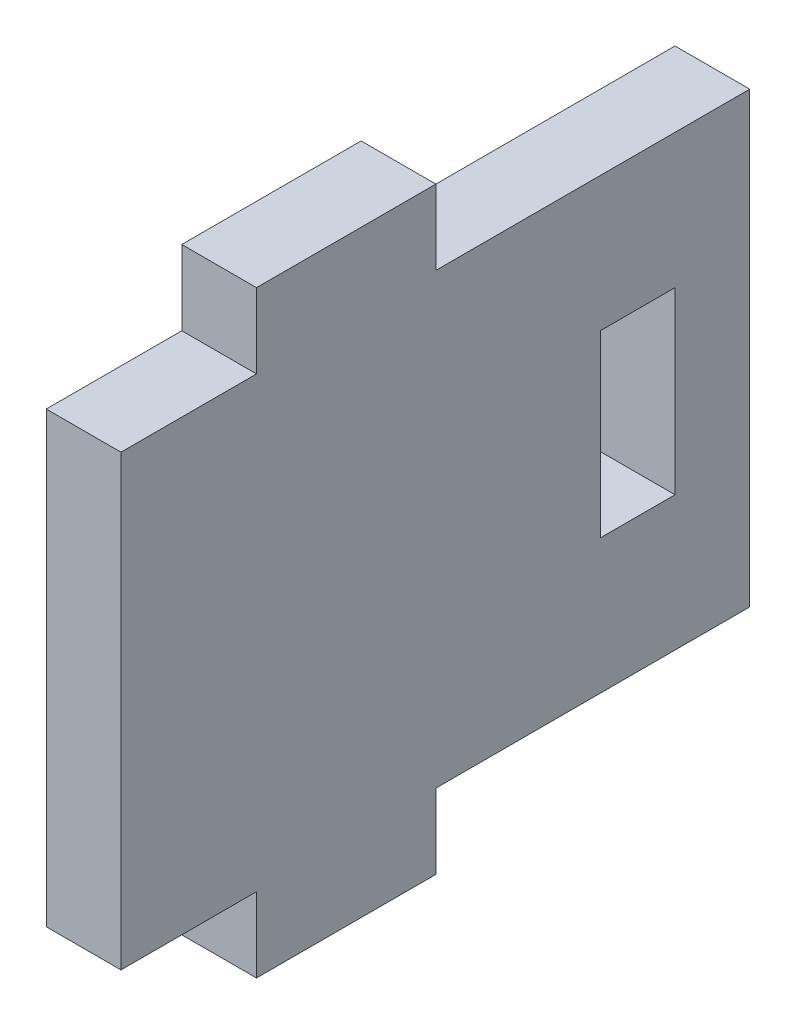
SolidWorks part; units mm, degrees
ref_plane "Front Plane" through (0, 0, 0) normal (0, 0, 1) x (1, 0, 0)
ref_plane "Top Plane" through (0, 0, 0) normal (0, 1, 0) x (1, 0, 0)
ref_plane "Right Plane" through (0, 0, 0) normal (1, 0, 0) x (0, 0, -1)
sketch "Sketch1" plane through (0, 0, 0) normal (1, 0, 0) x (0, 0, -1)
  line L0 (0, 15) -> (9.0664, 15)
  line L1 (9.0664, 15) -> (9.0664, 20)
  line L2 (9.0664, 20) -> (21.0664, 20)
  line L3 (21.0664, 20) -> (21.0664, 15)
  line L4 (21.0664, 15) -> (42.0664, 15)
  line L5 (42.0664, 15) -> (42.0664, -15)
  line L6 (60.2714, 0) -> (-60.2714, 0) construction
  line L7 (0, 15) -> (0, -15)
  line L8 (-1.9336, 14) -> (-1.9336, -14) construction
  line L9 (-1.9336, 14) -> (32.0664, 14) construction
  line L12 (32.0664, 14) -> (32.0664, -14) construction
  line L13 (32.0664, 6) -> (37.0664, 6)
  line L14 (32.0664, 6) -> (32.0664, -6)
  line L16 (37.0664, 6) -> (37.0664, -6)
  line L17 (-1.9336, -14) -> (32.0664, -14) construction
  line L18 (32.0664, -6) -> (37.0664, -6)
  line L19 (21.0664, -15) -> (42.0664, -15)
  line L20 (21.0664, -20) -> (21.0664, -15)
  line L21 (9.0664, -20) -> (21.0664, -20)
  line L22 (9.0664, -15) -> (9.0664, -20)
  line L23 (0, -15) -> (9.0664, -15)
  point P9 (0, 0)
  point P13 (57.3885, 0)
  point P16 (15.0664, 14)
  point P17 (15.0664, 20)
  point P22 (-60.2714, 0)
  point P25 (-1.9336, 0)
  point P26 (37.0664, 0)
  point P27 (32.0664, 0)
  point P28 (0, 0)
  point P29 (42.0664, 0)
  dimension "D1" = 12
  dimension "D2" = 5
  dimension "D3" = 28
  dimension "D4" = 34
  dimension "D5" = 12
  dimension "D6" = 5
  dimension "D7" = 30
extrude "Boss-Extrude1" add sketch "Sketch1" along normal blind 5
